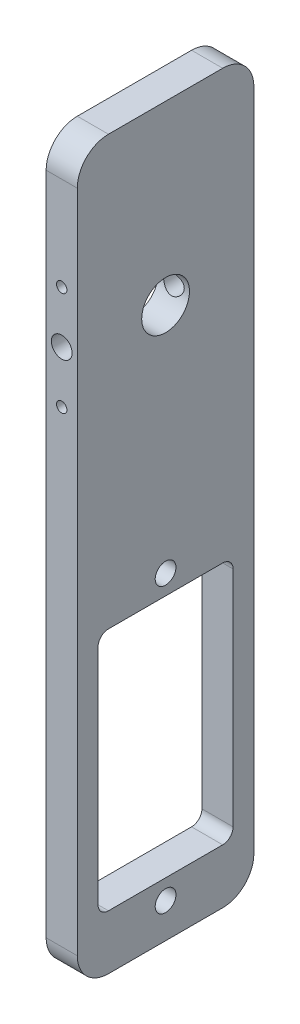
SolidWorks part; units mm, degrees
ref_plane "Спереди" through (0, 0, 0) normal (0, 0, 1) x (1, 0, 0)
ref_plane "Сверху" through (0, 0, 0) normal (0, 1, 0) x (1, 0, 0)
ref_plane "Справа" through (0, 0, 0) normal (1, 0, 0) x (0, 0, -1)
sketch "Sketch1" plane through (0, 0, 0) normal (1, 0, 0) x (0, 0, -1)
  line L0 (0, 0) -> (0, 70) construction
  line L1 (-5.5, 0) -> (5.5, 0)
  line L2 (-6.5, 27.75) -> (-6.5, 6.25)
  line L3 (-5.5, 70) -> (5.5, 70)
  line L4 (8.5, 3) -> (8.5, 67)
  line L5 (-5.5, 28.75) -> (5.5, 28.75)
  line L6 (-8.5, 3) -> (-8.5, 67)
  line L7 (-5.5, 5.25) -> (5.5, 5.25)
  line L8 (6.5, 27.75) -> (6.5, 6.25)
  line L9 (6.5, 17) -> (-6.5, 17) construction
  line L10 (-8.5, 35) -> (8.5, 35) construction
  circle A0 centre (0, 3.35) radius 1
  circle A1 centre (0, 30.65) radius 1
  arc A2 (-6.5, 6.25) -> (-5.5, 5.25) centre (-5.5, 6.25) ccw
  arc A3 (5.5, 5.25) -> (6.5, 6.25) centre (5.5, 6.25) ccw
  arc A4 (5.5, 28.75) -> (6.5, 27.75) centre (5.5, 27.75) cw
  arc A5 (-5.5, 28.75) -> (-6.5, 27.75) centre (-5.5, 27.75) ccw
  arc A6 (-8.5, 67) -> (-5.5, 70) centre (-5.5, 67) cw
  arc A7 (5.5, 70) -> (8.5, 67) centre (5.5, 67) cw
  arc A8 (5.5, 0) -> (8.5, 3) centre (5.5, 3) ccw
  arc A9 (-8.5, 3) -> (-5.5, 0) centre (-5.5, 3) ccw
  circle A15 centre (0, 53) radius 2.3
  point P11 (0, 5.25)
  point P12 (0, 28.75)
  point P23 (-6.5, 5.25)
  point P26 (6.5, 5.25)
  point P29 (6.5, 28.75)
  point P32 (-6.5, 28.75)
  point P35 (-8.5, 70)
  point P38 (8.5, 70)
  point P41 (8.5, 0)
  point P44 (-8.5, 0)
  dimension "D5" = 2
  dimension "D8" = 1
  dimension "D9" = 3
  dimension "D10" = 4.6
  dimension "D1" = 17
  dimension "D2" = 70
  dimension "D3" = 13
  dimension "D4" = 23.5
  dimension "D6" = 27.3
  dimension "D7" = 17
  dimension "D11" = 17
extrude "Boss-Extrude1" add sketch "Sketch1" along normal blind 3
sketch "Sketch2" plane through (0, 0, -8.5) normal (0, 0, -1) x (-1, 0, 0)
  line L0 (-1.5, 67) -> (-1.5, 3) construction
  line L1 (-3, 67) -> (0, 67) construction
  line L2 (-3, 3) -> (0, 3) construction
  line L3 (-3, 53) -> (0, 53) construction
  line L4 (-3, 3) -> (-3, 67) construction
  line L5 (0, 3) -> (0, 67) construction
  line L6 (-3, 70) -> (0, 70) construction
  circle A0 centre (-1.5, 58) radius 0.5
  circle A1 centre (-1.5, 48) radius 0.5
  circle A2 centre (-1.5, 53) radius 1
  dimension "D3" = 1
  dimension "D4" = 2
  dimension "D1" = 17
  dimension "D2" = 10
extrude "Cut-Extrude1" cut sketch "Sketch2" against normal through all
equation "\"12ю5\"=12"
